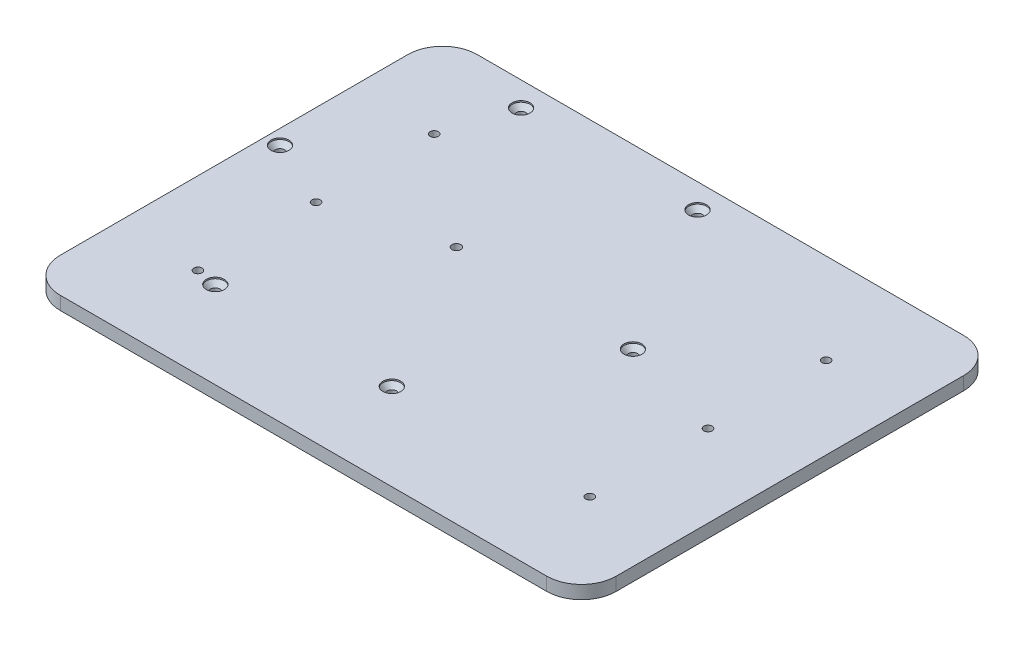
SolidWorks part; units mm, degrees
material "6061 Alloy"
ref_plane "Front Plane" through (0, 0, 0) normal (0, 0, 1) x (1, 0, 0)
ref_plane "Top Plane" through (0, 0, 0) normal (0, 1, 0) x (1, 0, 0)
ref_plane "Right Plane" through (0, 0, 0) normal (1, 0, 0) x (0, 0, -1)
sketch "Sketch1" plane through (0, 0, 0) normal (0, 1, 0) x (1, 0, 0)
  line L1 (-175, -150) -> (175, -150)
  line L2 (-200, -125) -> (-200, 125)
  line L3 (-175, 150) -> (175, 150)
  line L4 (200, -125) -> (200, 125)
  line L5 (-200, -150) -> (200, 150) construction
  line L6 (-200, 150) -> (200, -150) construction
  arc A0 (175, 150) -> (200, 125) centre (175, 125) cw
  arc A1 (175, -150) -> (200, -125) centre (175, -125) ccw
  arc A2 (-200, 125) -> (-175, 150) centre (-175, 125) cw
  arc A3 (-175, -150) -> (-200, -125) centre (-175, -125) cw
  point P0 (0, 0)
  dimension "D3" = 25
  dimension "D1" = 400
  dimension "D2" = 300
extrude "Extrude1" add sketch "Sketch1" along normal blind 9.525
sketch "Sketch5" plane through (0, 9.525, 0) normal (0, 1, 0) x (1, 0, 0)
  circle A0 centre (-62.5, 22.525) radius 3.175
  dimension "D1" = 6.35
  dimension "D2" = 62.5
  dimension "D3" = 22.525
extrude "Extrude2" cut sketch "Sketch5" against normal through all
hole_wizard "CSK for 1/4 Flat Head Machine Screw1" positions "Sketch4" profile "Sketch3" countersink size "1/4" standard "Ansi Inch" end condition through all
sketch "Sketch4" plane through (0, 9.525, 0) normal (0, 1, 0) x (-1, 0, 0)
  line L2 (62.5, -22.525) -> (162.6378, -22.525) construction
  line L3 (144.7724, -70.025) -> (62.5, -22.525) construction
  circle A1 centre (62.5, -22.525) radius 95 construction
  circle A2 centre (62.5, -22.525) radius 127 construction
  point P32 (189.5, -22.525)
  dimension "D1" = 190
  dimension "D2" = 254
  dimension "D3" = 30
sketch "Sketch3" plane through (-189.5, 9.525, -22.525) normal (1, 0, 0) x (0, 0, 1)
  line L0 (0, 0) -> (0, 9.525)
  line L1 (0, 9.525) -> (3.3782, 9.525)
  line L2 (3.3782, 9.525) -> (3.3782, 4.5209)
  line L3 (3.3782, 4.5209) -> (6.4389, 1)
  line L4 (6.4389, 1) -> (6.4389, 0)
  line L6 (6.4389, 0) -> (0, 0)
  line L7 (-3.3782, 4.5209) -> (-6.4389, 1) construction
  line L11 (0, -6.35) -> (0, 107.95) construction
  dimension "Thru Hole Dia." = 6.7564
  dimension "Thru Hole Depth" = 9.525
  dimension "C'Sink Dia." = 12.8778
  dimension "C'Sink Angle" = 82
  dimension "Head Clearance" = 1
pattern_circular "CirPattern1" count 6 over 360 about axis through (-62.5, 0, -22.525) along (0, 1, 0) of "CSK for 1/4 Flat Head Machine Screw1"
hole_wizard "Tapped Hole for #10-32 Helicoil1" positions "Sketch7" profile "Sketch6" tap size "#10-32" standard "Helicoil® Inch" end condition through all
sketch "Sketch7" plane through (0, 9.525, 0) normal (0, 1, 0) x (-1, 0, 0)
  point P0 (-141, 85)
  point P1 (141, -85)
  point P3 (141, 0)
  point P5 (141, 85)
  point P7 (-141, -85)
  point P9 (-141, 0)
  dimension "D1" = 282
  dimension "D2" = 141
  dimension "D3" = 85
  dimension "D4" = 85
sketch "Sketch6" plane through (141, 9.525, 85) normal (1, 0, 0) x (0, 0, 1)
  line L0 (0, 0) -> (0, 9.525)
  line L1 (0, 9.525) -> (2.5527, 9.525)
  line L3 (2.5527, 9.525) -> (2.5527, 8.556)
  line L4 (2.5527, 8.556) -> (2.968, 8.556)
  line L5 (2.968, 8.556) -> (2.968, 0)
  line L7 (2.968, 0) -> (0, 0)
  line L11 (0, -6.35) -> (0, 107.95) construction
  dimension "Thru Tap Drill Dia." = 5.1054
  dimension "Thru Tap Drill Depth" = 9.525
  dimension "Thread Major Dia." = 5.936
  dimension "Thread Depth" = 8.556
